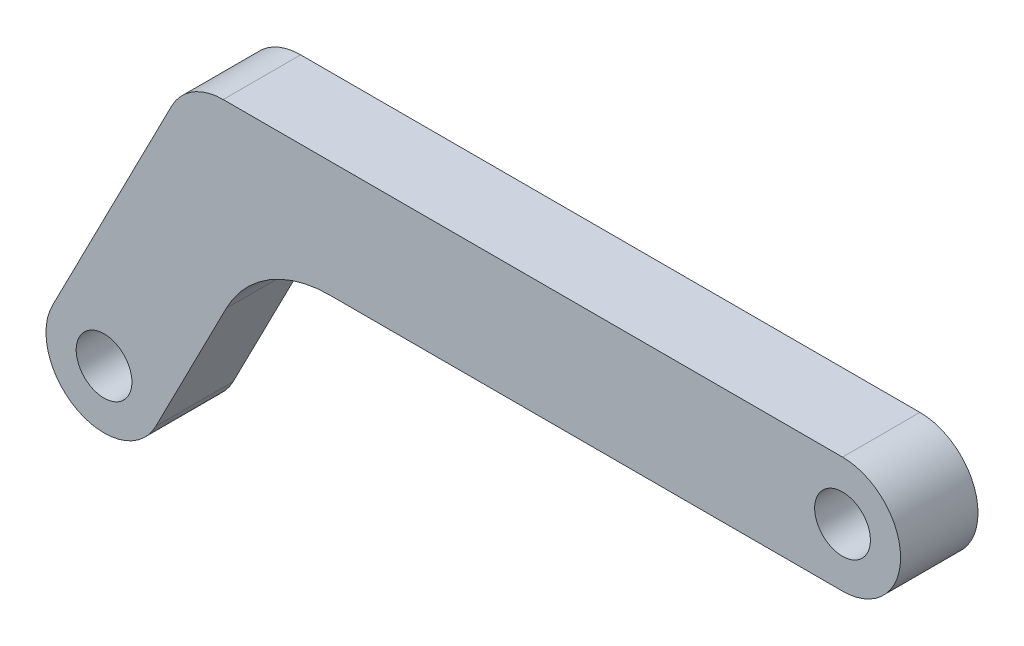
SolidWorks part; units mm, degrees
ref_plane "Front Plane" through (0, 0, 0) normal (0, 0, 1) x (1, 0, 0)
ref_plane "Top Plane" through (0, 0, 0) normal (0, 1, 0) x (1, 0, 0)
ref_plane "Right Plane" through (0, 0, 0) normal (1, 0, 0) x (0, 0, -1)
sketch "Sketch1" plane through (0, 0, 0) normal (0, 0, 1) x (1, 0, 0)
  line L0 (-64.8124, -16.8758) -> (-55.0372, 2.1742)
  line L1 (-50.8, 4.7625) -> (0, 4.7625)
  line L2 (-56.3379, -21.2242) -> (-50.5471, -9.939)
  line L3 (-42.0727, -4.7625) -> (0, -4.7625)
  arc A0 (0, -4.7625) -> (0, 4.7625) centre (0, 0) ccw
  arc A1 (-64.8124, -16.8758) -> (-56.3379, -21.2242) centre (-60.5751, -19.05) ccw
  arc A2 (-50.8, 4.7625) -> (-55.0372, 2.1742) centre (-50.8, 0) ccw
  arc A3 (-50.5471, -9.939) -> (-42.0727, -4.7625) centre (-42.0727, -14.2875) cw
  circle A4 centre (0, 0) radius 2.286
  circle A5 centre (-60.5751, -19.05) radius 2.286
  dimension "D1" = 9.525
  dimension "D5" = 9.525
  dimension "D6" = 4.572
  dimension "D7" = 4.572
  dimension "D2" = 63.5
  dimension "D3" = 19.05
  dimension "D4" = 50.8
extrude "Boss-Extrude1" add sketch "Sketch1" along normal blind 6.35
